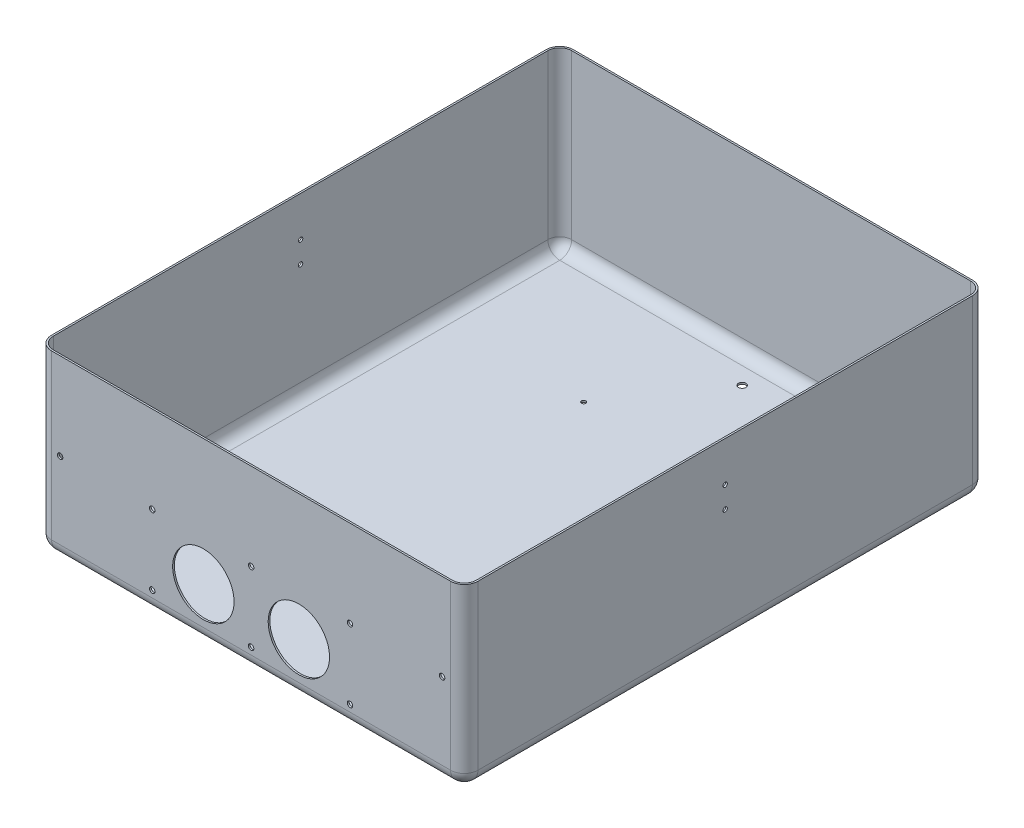
SolidWorks part; units mm, degrees
ref_plane "front" through (0, 0, 0) normal (0, 0, 1) x (1, 0, 0)
ref_plane "top" through (0, 0, 0) normal (0, 1, 0) x (1, 0, 0)
ref_plane "right" through (0, 0, 0) normal (1, 0, 0) x (0, 0, -1)
sketch "Sketch1" plane through (0, 0, 0) normal (0, 1, 0) x (1, 0, 0)
  line L1 (-198.4375, 485.775) -> (198.4375, 485.775)
  line L2 (-198.4375, 485.775) -> (-198.4375, 0)
  line L3 (-198.4375, 0) -> (198.4375, 0)
  line L4 (198.4375, 485.775) -> (198.4375, 0)
  dimension "D2" = 396.875
  dimension "D3" = 485.775
extrude "Extrude1" add sketch "Sketch1" along normal blind 165.1
fillet "Fillet1" radius 12.7 4 edges at (-198.4375, 82.55, 0) (-198.4375, 82.55, -485.775) (198.4375, 82.55, -485.775) (198.4375, 82.55, 0)
fillet "Fillet2" radius 12.7 8 edges at (194.7178, 0, -3.7197) (198.4375, 0, -242.8875) (194.7178, 0, -482.0553) (0, 0, -485.775) (-194.7178, 0, -482.0553) (-198.4375, 0, -242.8875) (-194.7178, 0, -3.7197) (0, 0, 0)
shell "Shell1" thickness 1.6002
sketch "Sketch2" plane through (0, 0, 0) normal (0, 0, 1) x (1, 0, 0)
  line L0 (0, 0) -> (0, -55.3243) construction
  line L1 (-185.7375, 165.1) -> (185.7375, 165.1) construction
  circle A4 centre (-44.45, 47.625) radius 28.575
  circle A5 centre (44.45, 47.625) radius 28.575
  circle A6 centre (-92.075, 84.1502) radius 2.5527
  circle A7 centre (-92.075, 19.05) radius 2.5527
  circle A8 centre (92.075, 19.05) radius 2.5527
  circle A9 centre (92.075, 84.1502) radius 2.5527
  circle A10 centre (0, 84.1502) radius 2.5527
  circle A11 centre (0, 19.05) radius 2.5527
  circle A12 centre (-177.8, 84.1502) radius 2.5527
  circle A13 centre (177.8, 84.1502) radius 2.5527
  point P4 (0, 14.2875)
  dimension "D4" = 28.575
  dimension "D5" = 57.15
  dimension "D8" = 5.1054
  dimension "D2" = 117.475
  dimension "D3" = 36.5252
  dimension "D6" = 88.9
  dimension "D7" = 47.625
  dimension "D9" = 19.05
  dimension "D10" = 84.1502
  dimension "D11" = 92.075
  dimension "D12" = 177.8
  dimension "D13" = 65.1002
extrude "Cut-Extrude1" cut sketch "Sketch2" against normal blind 25.4
sketch "Sketch3" plane through (0, 0, 0) normal (1, 0, 0) x (0, 0, -1)
  line L0 (12.7, 165.1) -> (473.075, 165.1) construction
  line L1 (485.775, 165.1) -> (485.775, 12.7) construction
  line L2 (422.275, 63.5) -> (422.275, 85.1156) construction
  line L3 (422.275, 63.5) -> (440.4352, 63.5) construction
  circle A0 centre (422.275, 63.5) radius 28.575
  circle A1 centre (450.85, 92.075) radius 3.4544
  circle A2 centre (393.7, 92.075) radius 3.4544
  circle A3 centre (393.7, 34.925) radius 3.4544
  circle A4 centre (450.85, 34.925) radius 3.4544
  dimension "D1" = 57.15
  dimension "D6" = 6.9088
  dimension "D2" = 101.6
  dimension "D3" = 63.5
  dimension "D4" = 28.575
  dimension "D5" = 28.575
extrude "Cut-Extrude2" [suppressed] cut sketch "Sketch3" against normal through all
sketch "Sketch4" plane through (0, 0, 0) normal (1, 0, 0) x (0, 0, -1)
  line L0 (-1.9939, 163.5252) -> (-1.9939, 166.0652)
  line L1 (0.2159, 168.275) -> (489.3691, 168.275)
  line L2 (-1.9939, 163.5252) -> (-3.5941, 163.5252)
  line L3 (-3.5941, 166.0652) -> (-3.5941, 163.5252)
  line L4 (0.2159, 169.8752) -> (489.3691, 169.8752)
  line L5 (12.7, 165.1) -> (0, 165.1) construction
  line L6 (3.719, 169.133) -> (3.0566, 168.371)
  line L7 (489.3691, 169.8752) -> (489.3691, 168.275)
  line L8 (242.8875, 165.1) -> (242.8875, 103.9257) construction
  line L9 (3.0566, 168.371) -> (8.3438, 168.371)
  line L10 (12.7, 165.1) -> (473.075, 165.1) construction
  line L11 (0, 12.7) -> (0, 165.1) construction
  line L12 (9.6626, 169.8752) -> (0.4615, 169.8752)
  line L13 (21.0312, 168.2242) -> (6.7437, 168.2242)
  line L14 (6.7437, 168.2242) -> (1.9812, 163.4617)
  line L15 (9.6626, 171.4754) -> (0.4615, 171.4754)
  line L16 (-8.9972, 166.0021) -> (-10.6006, 166.0021)
  line L17 (9.6626, 171.4754) -> (9.6626, 169.8752)
  line L18 (1.9812, 163.4617) -> (1.9812, 147.5867)
  line L19 (1.9812, 147.5867) -> (6.7437, 142.8242)
  line L20 (2.9972, 148.0075) -> (7.4621, 143.5426)
  line L21 (2.9972, 163.0409) -> (2.9972, 148.0075)
  line L22 (7.1645, 167.2082) -> (2.9972, 163.0409)
  line L23 (21.0312, 167.2082) -> (7.1645, 167.2082)
  line L24 (21.0312, 168.2242) -> (21.0312, 167.2082)
  line L25 (6.7437, 142.8242) -> (7.4621, 143.5426)
  line L26 (5.7002, 175.7883) -> (5.7002, 153.3652) construction
  line L27 (7.6814, 169.133) -> (8.3438, 168.371)
  line L28 (3.719, 169.133) -> (3.719, 171.6277)
  line L29 (4.3624, 165.843) -> (-1.9939, 165.843) construction
  line L30 (7.6814, 169.133) -> (7.6814, 171.6277)
  line L31 (3.719, 171.6277) -> (1.7251, 171.6277)
  line L32 (7.6814, 171.6277) -> (9.6753, 171.6277)
  line L33 (15.4559, 171.8225) -> (15.4559, 163.7975) construction
  line L34 (18.6309, 165.7761) -> (12.2809, 165.7761)
  line L35 (12.2809, 165.7761) -> (12.2809, 166.9191)
  line L36 (12.2809, 166.9191) -> (13.4747, 166.9191)
  line L37 (13.4747, 166.9191) -> (13.4747, 170.0169)
  line L38 (13.4747, 170.0169) -> (11.4808, 170.0169)
  line L39 (18.6309, 165.7761) -> (18.6309, 166.9191)
  line L40 (18.6309, 166.9191) -> (17.4371, 166.9191)
  line L41 (17.4371, 166.9191) -> (17.4371, 170.0169)
  line L42 (17.4371, 170.0169) -> (19.431, 170.0169)
  line L43 (5.3412, 168.275) -> (4.261, 168.275)
  line L44 (0.0918, 164.6147) -> (1.7734, 164.6147)
  line L47 (1.6002, 12.7) -> (1.6002, 165.1) construction
  arc A0 (-1.9939, 166.0652) -> (0.2159, 168.275) centre (0.2159, 166.0652) cw
  arc A1 (-3.5941, 166.0652) -> (0.2159, 169.8752) centre (0.2159, 166.0652) cw
  arc A2 (11.4808, 170.0169) -> (19.431, 170.0169) centre (15.4559, 165.065) cw
  arc A3 (-3.598, 166.0021) -> (-10.6006, 166.0021) centre (-7.0993, 166.1668) cw
  arc A4 (0.4615, 169.8752) -> (-3.598, 166.0021) centre (0.4615, 165.8112) ccw
  arc A5 (-5.1964, 166.0773) -> (-8.9972, 166.0021) centre (-7.0993, 166.1668) cw
  arc A6 (0.4615, 171.4754) -> (-5.1964, 166.0773) centre (0.4615, 165.8112) ccw
  arc A7 (1.7251, 171.6277) -> (9.6753, 171.6277) centre (5.7002, 166.6759) cw
  arc A8 (4.261, 168.275) -> (5.0186, 167.3888) centre (4.261, 167.5081) cw
  arc A9 (1.7734, 164.6147) -> (5.0186, 167.3888) centre (1.7734, 167.8998) ccw
  arc A11 (0.0918, 164.6147) -> (0.0918, 168.1719) centre (0.0918, 166.3933) cw
  point P46 (5.7002, 168.371)
  point P47 (5.7002, 153.5157)
  point P62 (15.4559, 165.7761)
  point P77 (3.6195, 165.1)
  dimension "D9" = 3.81
  dimension "D4" = 4.064
  dimension "D11" = 14.859
  dimension "D13" = 1.905
  dimension "D19" = 0.762
  dimension "D24" = 6.35
  dimension "D2" = 1.6002
  dimension "D3" = 3.175
  dimension "D5" = 6.35
  dimension "D6" = 41
  dimension "D7" = 246.4816
  dimension "D8" = 1.9939
  dimension "D14" = 8.8138
  dimension "D15" = 15.875
  dimension "D16" = 45
  dimension "D17" = 45
  dimension "D20" = 7.9502
  dimension "D21" = 3.9624
  dimension "D22" = 3.9624
  dimension "D23" = 0.0508
  dimension "D25" = 6.35
  dimension "D26" = 25.4
  dimension "D27" = 7.9502
  dimension "D28" = 3.9624
  dimension "D29" = 1.143
  dimension "D30" = 19.05
  dimension "D31" = 19.05
  dimension "D32" = 13.4747
  dimension "D33" = 0.381
  dimension "D34" = 5.5753
  dimension "D35" = 6.3563
  dimension "D10" = 1.6002
  dimension "D12" = 1.6002
  dimension "D18" = 1.016
sketch "Sketch5" plane through (0, 0, 0) normal (0, -1, 0) x (1, 0, 0)
  line L0 (-166.6875, -384.175) -> (-132.2839, -384.175) construction
  line L1 (-166.6875, -384.175) -> (-166.6875, -347.3354) construction
  line L2 (185.7375, -485.775) -> (-185.7375, -485.775) construction
  line L3 (-198.4375, -473.075) -> (-198.4375, -12.7) construction
  line L5 (-184.8358, -366.0267) -> (-148.5392, -366.0267) construction
  line L6 (-184.8358, -366.0267) -> (-184.8358, -402.3233) construction
  line L7 (-184.8358, -402.3233) -> (-148.5392, -402.3233) construction
  line L8 (-148.5392, -366.0267) -> (-148.5392, -402.3233) construction
  circle A0 centre (-166.6875, -384.175) radius 15.367
  circle A1 centre (-181.2925, -369.57) radius 2.3813
  circle A2 centre (-152.0825, -369.57) radius 2.3813
  circle A3 centre (-181.2925, -398.78) radius 2.3813
  circle A4 centre (-152.0825, -398.78) radius 2.3813
  circle A5 centre (-166.6875, -434.975) radius 11.1125
  circle A6 centre (-166.6875, -420.751) radius 2.3813
  circle A7 centre (-166.6875, -449.199) radius 2.3813
  point P20 (-166.6875, -366.0267)
  point P21 (-184.8358, -384.175)
  dimension "D1" = 29.21
  dimension "D3" = 30.734
  dimension "D4" = 4.7625
  dimension "D8" = 22.225
  dimension "D10" = 14.224
  dimension "D11" = 14.224
  dimension "D12" = 50.8
  dimension "D2" = 29.21
  dimension "D5" = 101.6
  dimension "D6" = 31.75
  dimension "D7" = 36.2966
extrude "Cut-Extrude3" [suppressed] cut sketch "Sketch5" against normal through all
sketch "Sketch6" plane through (0, 0, 0) normal (0, 1, 0) x (1, 0, 0)
  line L1 (185.7375, 485.775) -> (-185.7375, 485.775) construction
  circle A0 centre (0, 457.2) radius 3.4544
  circle A1 centre (0, 457.2) radius 12.7 construction
  dimension "D3" = 6.9088
  dimension "D1" = 25.4
  dimension "D2" = 28.575
extrude "Cut-Extrude5" cut sketch "Sketch6" along normal through all
sketch "Sketch7" plane through (0, 0, 0) normal (0, 1, 0) x (1, 0, 0)
  line L0 (-50.8, 32.8633) -> (-50.8, 162.9428) construction
  line L1 (0, 0) -> (0, 85.0306) construction
  line L2 (-185.7375, 1.6002) -> (185.7375, 1.6002) construction
  line L3 (185.7375, 484.1748) -> (-185.7375, 484.1748) construction
  circle A0 centre (-60.325, 103.2002) radius 1.9812
  circle A2 centre (-60.325, 369.8748) radius 1.9812
  circle A5 centre (60.325, 369.8748) radius 1.9812
  circle A7 centre (60.325, 103.2002) radius 1.9812
  dimension "D5" = 3.9624
  dimension "D1" = 9.525
  dimension "D2" = 50.8
  dimension "D3" = 101.6
  dimension "D4" = 114.3
extrude "Cut-Extrude6" cut sketch "Sketch7" along normal through all
sketch "Sketch8" plane through (198.4375, 0, 0) normal (1, 0, 0) x (0, 0, -1)
  line L0 (12.7, 165.1) -> (473.075, 165.1) construction
  circle A0 centre (242.8875, 127.762) radius 2.0447
  circle A1 centre (242.8875, 107.8484) radius 2.0447
  dimension "D1" = 4.0894
  dimension "D2" = 37.338
  dimension "D3" = 19.9136
  dimension "D4" = 242.8875
extrude "Cut-Extrude7" cut sketch "Sketch8" against normal up to next
mirror "Mirror1" about plane through (0, 0, 0) normal (1, 0, 0) of "Cut-Extrude7"
ref_plane "Plane1" through (0, 0, -242.8875) normal (0, 0, 1) x (1, 0, 0)
sketch "Sketch10" [suppressed] plane through (0, 0, 0) normal (0, 0, 1) x (1, 0, 0)
  line L0 (-185.7375, 165.1) -> (185.7375, 165.1) construction
  circle A0 centre (-133.6548, 127.762) radius 2.0447
  circle A1 centre (-133.6548, 107.8484) radius 2.0447
  circle A2 centre (133.6548, 127.762) radius 2.0447
  circle A3 centre (133.6548, 107.8484) radius 2.0447
  circle A4 centre (0, 84.1502) radius 2.5527 construction
  dimension "D1" = 19.9136
  dimension "D2" = 37.338
  dimension "D3" = 4.0894
  dimension "D4" = 133.6548
  dimension "D5" = 133.6548
extrude "Cut-Extrude8" [suppressed] cut sketch "Sketch10" against normal up to next
mirror "Mirror2" [suppressed] about plane through (0, 0, -242.8875) normal (0, 0, 1)
